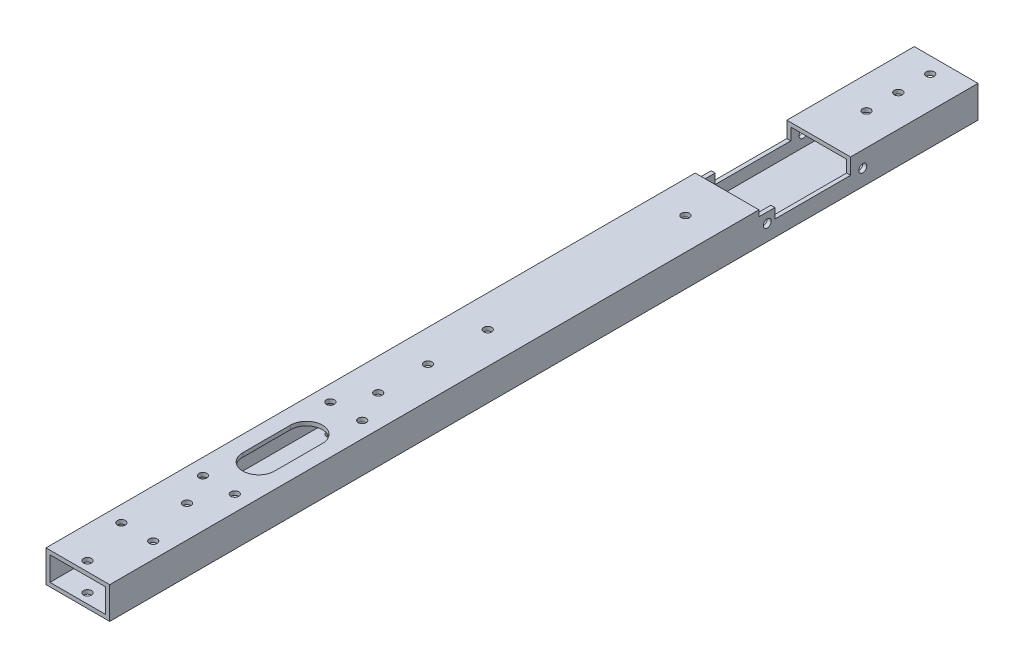
SolidWorks part; units mm, degrees
ref_plane "Front Plane" through (0, 0, 0) normal (0, 0, 1) x (1, 0, 0)
ref_plane "Top Plane" through (0, 0, 0) normal (0, 1, 0) x (1, 0, 0)
ref_plane "Right Plane" through (0, 0, 0) normal (1, 0, 0) x (0, 0, -1)
sketch "Sketch1" plane through (0, 0, 0) normal (0, 0, 1) x (1, 0, 0)
  line L1 (25.4, -12.7) -> (-25.4, -12.7)
  line L2 (25.4, -12.7) -> (25.4, 12.7)
  line L3 (25.4, 12.7) -> (-25.4, 12.7)
  line L4 (-25.4, -12.7) -> (-25.4, 12.7)
  line L5 (25.4, -12.7) -> (-25.4, 12.7) construction
  line L6 (25.4, 12.7) -> (-25.4, -12.7) construction
  line L7 (22.225, -9.525) -> (-22.225, -9.525)
  line L8 (22.225, -9.525) -> (22.225, 9.525)
  line L9 (22.225, 9.525) -> (-22.225, 9.525)
  line L10 (-22.225, -9.525) -> (-22.225, 9.525)
  line L11 (22.225, -9.525) -> (-22.225, 9.525) construction
  line L12 (22.225, 9.525) -> (-22.225, -9.525) construction
  point P0 (0, 0)
  point P6 (0, 0)
  dimension "D1" = 50.8
  dimension "D2" = 25.4
  dimension "D3" = 44.45
  dimension "D4" = 19.05
extrude "Boss-Extrude1" add sketch "Sketch1" along normal blind 692.15
sketch "Sketch2" plane through (25.4, 0, 0) normal (1, 0, 0) x (0, 0, -1)
  line L0 (-692.15, 12.7) -> (0, 12.7) construction
  line L1 (-161.925, 12.7) -> (-101.6, 12.7)
  line L2 (-161.925, 12.7) -> (-161.925, 0)
  line L3 (-161.925, 0) -> (-101.6, 0)
  line L4 (-101.6, 12.7) -> (-101.6, 0)
  line L6 (0, -12.7) -> (0, 12.7) construction
  dimension "D1" = 60.325
  dimension "D2" = 12.7
  dimension "D3" = 101.6
extrude "Cut-Extrude1" cut sketch "Sketch2" against normal through all
sketch "Sketch3" plane through (25.4, 0, 0) normal (1, 0, 0) x (0, 0, -1)
  line L0 (0, 0) -> (-133.147, 0) construction
  line L1 (-161.925, 0) -> (-161.925, 9.525) construction
  circle A0 centre (-167.9999, 0) radius 3.175
  circle A1 centre (-91.8139, 0) radius 3.175
  point P7 (-161.925, 4.7625)
  dimension "D1" = 6.35
  dimension "D2" = 6.35
  dimension "D3" = 6.0749
  dimension "D4" = 9.7861
extrude "Cut-Extrude2" cut sketch "Sketch3" against normal through all
sketch "Sketch4" plane through (25.4, 0, 0) normal (1, 0, 0) x (0, 0, -1)
  line L1 (-161.925, 12.7) -> (-174.625, 12.7)
  line L2 (-161.925, 12.7) -> (-161.925, 7.9375)
  line L3 (-161.925, 7.9375) -> (-174.625, 7.9375)
  line L4 (-174.625, 12.7) -> (-174.625, 7.9375)
  dimension "D1" = 4.7625
  dimension "D2" = 12.7
extrude "Cut-Extrude3" cut sketch "Sketch4" against normal through all
sketch "Sketch5" plane through (0, 12.7, 0) normal (0, 1, 0) x (1, 0, 0)
  line L0 (0, -174.625) -> (0, -692.15) construction
  line L1 (-25.4, -174.625) -> (25.4, -174.625) construction
  line L2 (25.4, -692.15) -> (-25.4, -692.15) construction
  line L3 (-25.4, -478.1591) -> (25.4, -478.1591) construction
  line L4 (-25.4, -692.15) -> (-25.4, -174.625) construction
  line L5 (22.225, -167.9999) -> (25.4, -167.9999) construction
  line L6 (25.4, -692.15) -> (25.4, -174.625) construction
  line L7 (-25.4, -579.7591) -> (25.4, -579.7591) construction
  line L8 (-25.4, -644.8067) -> (25.4, -644.8067) construction
  circle A0 centre (0, -207.8596) radius 3.175
  circle A1 centre (0, -365.4407) radius 3.175
  circle A2 centre (0, -413.1114) radius 3.175
  circle A3 centre (0, -452.7591) radius 3.175
  circle A4 centre (-12.7, -478.1591) radius 3.175
  circle A5 centre (12.7, -478.1591) radius 3.175
  circle A6 centre (-12.7, -579.7591) radius 3.175
  circle A7 centre (12.7, -579.7591) radius 3.175
  circle A8 centre (0, -605.1591) radius 3.175
  circle A9 centre (-12.7, -644.8067) radius 3.175
  circle A10 centre (12.7, -644.8067) radius 3.175
  circle A11 centre (0, -684.4543) radius 3.175
  circle A12 centre (0, -548.0091) radius 2.0828
  circle A13 centre (0, -535.3091) radius 2.0828
  circle A14 centre (0, -522.6091) radius 2.0828
  circle A15 centre (0, -509.9091) radius 2.0828
  dimension "D1" = 39.8597
  dimension "D2" = 157.5811
  dimension "D3" = 47.6707
  dimension "D4" = 39.6476
  dimension "D6" = 12.7
  dimension "D8" = 12.7
  dimension "D9" = 25.4
  dimension "D11" = 12.7
  dimension "D12" = 39.6476
  dimension "D13" = 4.1656
  dimension "D14" = 31.75
  dimension "D5" = 25.4
  dimension "D7" = 101.6
  dimension "D10" = 39.6476
  dimension "D15" = 4
extrude "Cut-Extrude4" cut sketch "Sketch5" against normal through all
sketch "Sketch7" plane through (0, 12.7, 0) normal (0, 1, 0) x (1, 0, 0)
  line L0 (0, -548.0091) -> (0, -509.9091) construction
  line L1 (-12.7, -548.0091) -> (-12.7, -509.9091)
  line L2 (12.7, -548.0091) -> (12.7, -509.9091)
  arc A0 (-12.7, -548.0091) -> (12.7, -548.0091) centre (0, -548.0091) ccw
  arc A1 (12.7, -509.9091) -> (-12.7, -509.9091) centre (0, -509.9091) ccw
  point P4 (0, -528.9591)
  dimension "D1" = 12.7
extrude "Cut-Extrude5" cut sketch "Sketch7" against normal blind 3.175
sketch "Sketch8" plane through (0, 12.7, 0) normal (0, 1, 0) x (1, 0, 0)
  line L0 (0, -101.6) -> (0, 0) construction
  line L1 (-25.4, -101.6) -> (25.4, -101.6) construction
  circle A0 centre (0, -12.7) radius 3.175
  circle A1 centre (0, -38.1) radius 3.175
  circle A2 centre (0, -63.5) radius 3.175
  dimension "D1" = 6.35
  dimension "D2" = 12.7
  dimension "D3" = 3
extrude "Cut-Extrude6" cut sketch "Sketch8" against normal through all
